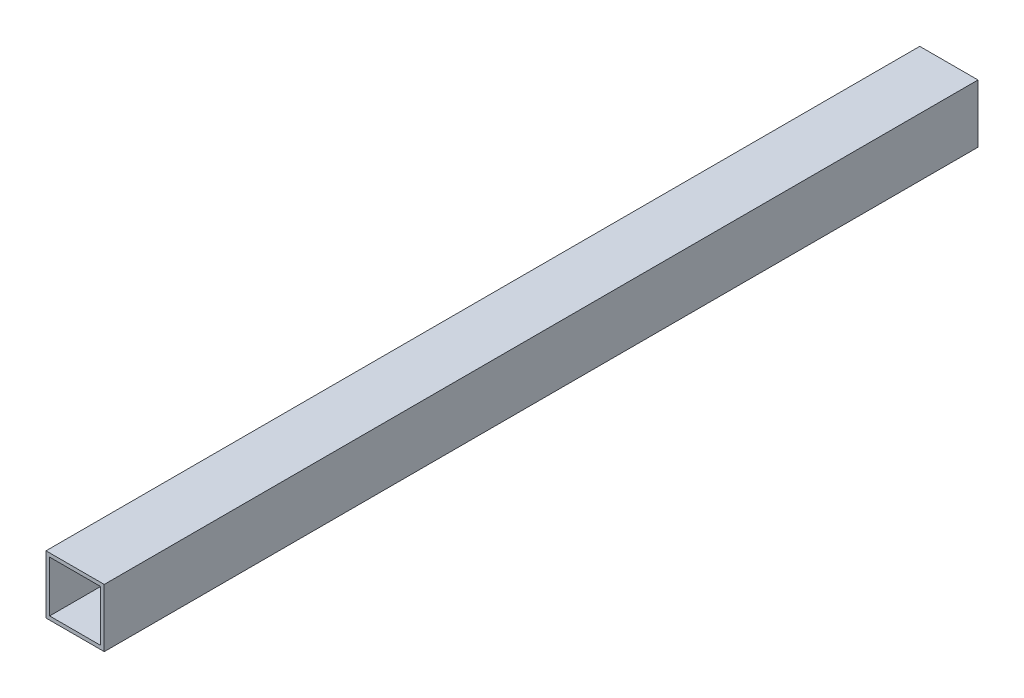
SolidWorks part; units mm, degrees
ref_plane "Front Plane" through (0, 0, 0) normal (0, 0, 1) x (1, 0, 0)
ref_plane "Top Plane" through (0, 0, 0) normal (0, 1, 0) x (1, 0, 0)
ref_plane "Right Plane" through (0, 0, 0) normal (1, 0, 0) x (0, 0, -1)
sketch "Sketch1" plane through (0, 0, 0) normal (0, 1, 0) x (1, 0, 0)
  line L1 (-12.7, -190.5) -> (12.7, -190.5)
  line L2 (-12.7, -190.5) -> (-12.7, 190.5)
  line L3 (-12.7, 190.5) -> (12.7, 190.5)
  line L4 (12.7, -190.5) -> (12.7, 190.5)
  line L5 (-12.7, -190.5) -> (12.7, 190.5) construction
  line L6 (-12.7, 190.5) -> (12.7, -190.5) construction
  point P0 (0, 0)
  dimension "D1" = 381
  dimension "D2" = 25.4
extrude "Boss-Extrude1" add sketch "Sketch1" along normal blind 25.4
sketch "Sketch3" plane through (0, 0, 190.5) normal (0, 0, 1) x (1, 0, 0)
  line L0 (12.7, 25.4) -> (12.7, 0) construction
  line L1 (-11.1125, 1.5875) -> (11.1125, 1.5875)
  line L2 (-11.1125, 1.5875) -> (-11.1125, 23.8125)
  line L3 (-11.1125, 23.8125) -> (11.1125, 23.8125)
  line L4 (11.1125, 1.5875) -> (11.1125, 23.8125)
  line L5 (-11.1125, 1.5875) -> (11.1125, 23.8125) construction
  line L6 (-11.1125, 23.8125) -> (11.1125, 1.5875) construction
  line L7 (-12.7, 25.4) -> (-12.7, 0) construction
  line L8 (-12.7, 0) -> (12.7, 0) construction
  line L9 (-12.7, 25.4) -> (12.7, 25.4) construction
  point P0 (0, 12.7)
  dimension "D1" = 1.5875
  dimension "D2" = 1.5875
  dimension "D3" = 1.5875
  dimension "D4" = 1.5875
extrude "Cut-Extrude2" cut sketch "Sketch3" against normal blind 381
